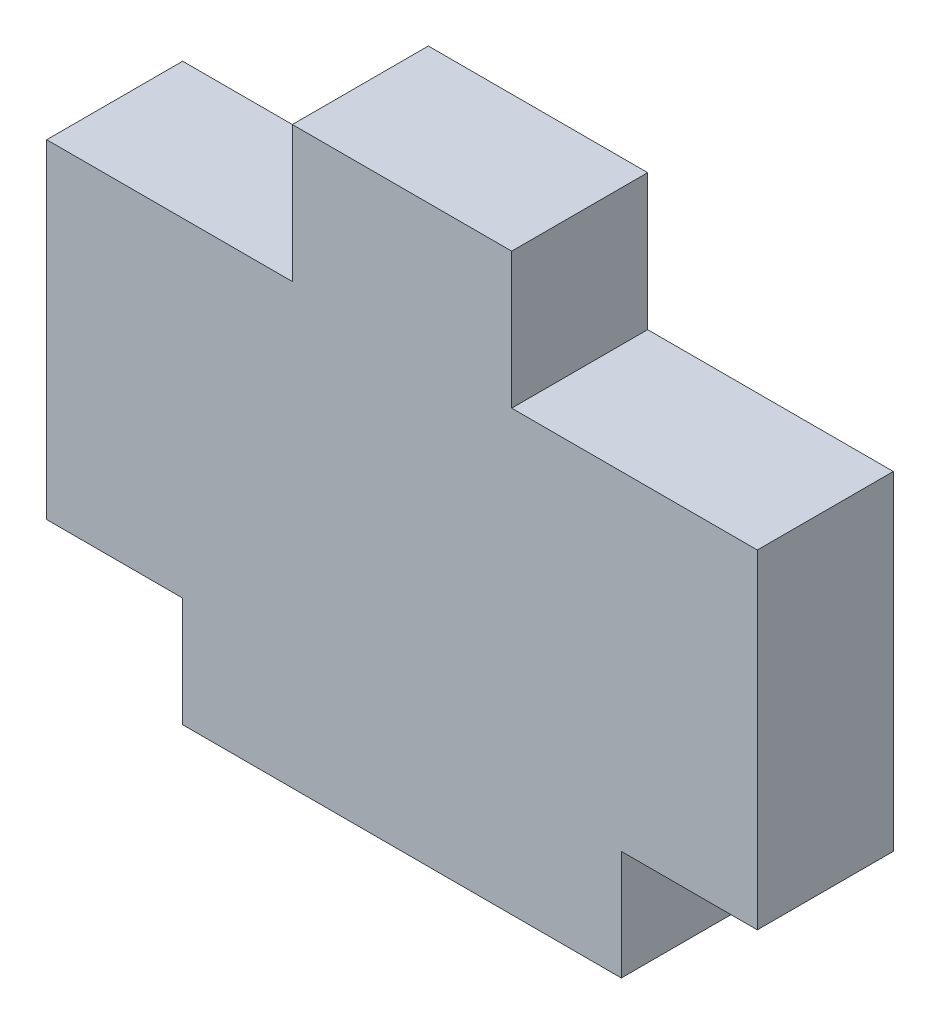
SolidWorks part; units mm, degrees
ref_plane "Front Plane" through (0, 0, 0) normal (0, 0, 1) x (1, 0, 0)
ref_plane "Top Plane" through (0, 0, 0) normal (0, 1, 0) x (1, 0, 0)
ref_plane "Right Plane" through (0, 0, 0) normal (1, 0, 0) x (0, 0, -1)
sketch "Model" plane through (0, 0, 0) normal (0, 0, 1) x (1, 0, 0)
  line L0 (10, 40) -> (32.4, 40)
  line L1 (-20, 0) -> (20, 0)
  line L2 (-32.4, 10) -> (-32.4, 40)
  line L3 (-32.4, 40) -> (-10, 40)
  line L4 (32.4, 10) -> (32.4, 40)
  line L5 (-32.4, 10) -> (-20, 10)
  line L8 (-20, 10) -> (-20, 0)
  line L9 (32.4, 10) -> (20, 10)
  line L12 (20, 10) -> (20, 0)
  line L14 (-10, 40) -> (-10, 52.4)
  line L15 (-10, 52.4) -> (10, 52.4)
  line L16 (10, 40) -> (10, 52.4)
  dimension "D2" = 20
  dimension "D8" = 30
  dimension "D11" = 12.4
  dimension "D9" = 12.4
  dimension "D3" = 22.4
  dimension "D4" = 10
extrude "Boss-Extrude1" add sketch "Model" along normal blind 12.4
equation "\"tab-width-small\" = 20mm ' Width of the small version of the Tab"
equation "\"material-thickness\" = 12.4mm"
equation "\"D11@Model\"= \"material-thickness\""
equation "\"D9@Model\" = \"material-thickness\""
equation "\"D1@Boss-Extrude1\" = \"material-thickness\""
equation "\"D2@Model\"=\"tab-width-small\""
equation "\"D3@Model\"=\"material-thickness\" + 10"
